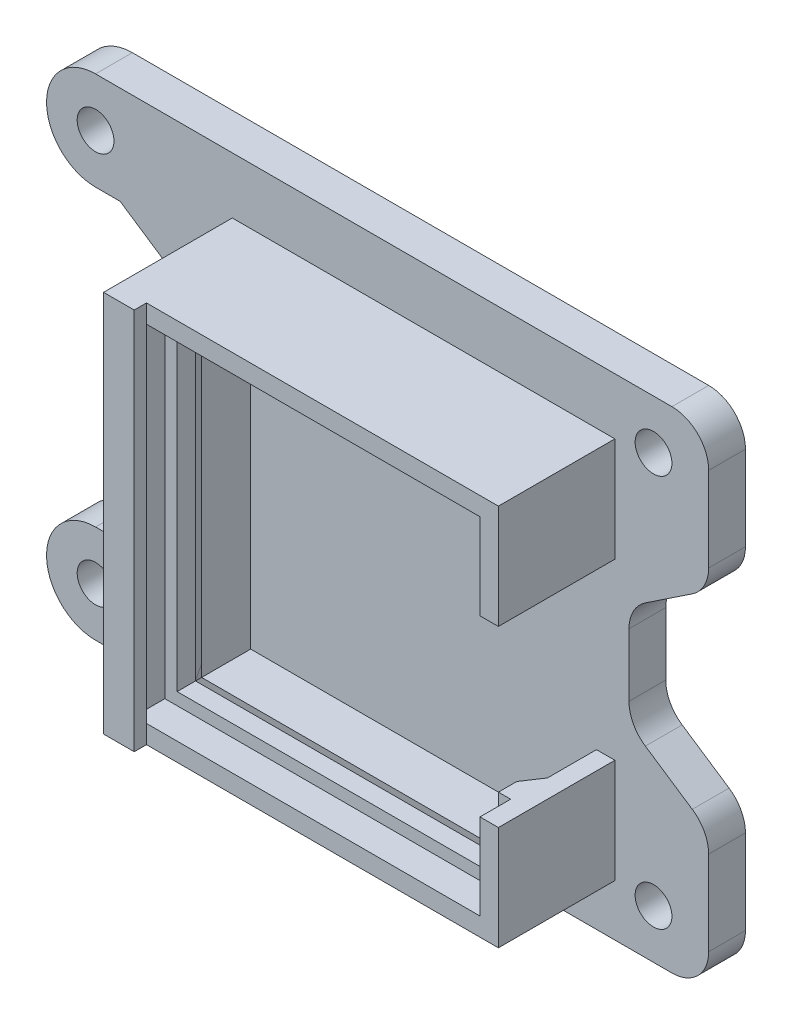
SolidWorks part; units mm, degrees
ref_plane "Alzado" through (0, 0, 0) normal (0, 0, 1) x (1, 0, 0)
ref_plane "Planta" through (0, 0, 0) normal (0, 1, 0) x (1, 0, 0)
ref_plane "Vista lateral" through (0, 0, 0) normal (1, 0, 0) x (0, 0, -1)
sketch "Croquis1" plane through (0, 0, 0) normal (0, 0, 1) x (1, 0, 0)
  line L0 (-52.1973, 0.4619) -> (-52.1973, 4.4619) construction
  line L1 (-2.1973, 16.4619) -> (-44.1973, 16.4619) construction
  line L2 (-52.1973, 4.4619) -> (-50.1973, 4.4619)
  line L3 (-52.1973, -3.5381) -> (-5.1973, -3.5381)
  line L5 (-44.1973, 24.4619) -> (-44.1973, 8.4619)
  line L6 (-44.1973, 8.4619) -> (-50.1973, 4.4619)
  line L7 (-52.1973, 32.4619) -> (-52.1973, 28.4619) construction
  line L8 (-44.1973, 24.4619) -> (-50.1973, 28.4619)
  line L9 (-52.1973, 36.4619) -> (-5.1973, 36.4619)
  line L10 (-52.1973, 28.4619) -> (-50.1973, 28.4619)
  line L11 (-2.1973, -0.5381) -> (-2.1973, 6.3563)
  line L13 (-3.5332, 8.8525) -> (-7.3614, 11.4046)
  line L14 (-8.6973, 13.9008) -> (-8.6973, 19.023)
  line L15 (-3.5332, 24.0713) -> (-7.3614, 21.5191)
  line L16 (-2.1973, 33.4619) -> (-2.1973, 26.5674)
  arc A0 (-52.1973, 36.4619) -> (-52.1973, 28.4619) centre (-52.1973, 32.4619) ccw
  circle A1 centre (-6.6973, 32.4619) radius 1.5
  circle A2 centre (-52.1973, 0.4619) radius 1.5
  circle A3 centre (-6.6973, 0.4619) radius 1.5
  circle A4 centre (-52.1973, 32.4619) radius 1.5
  arc A5 (-5.1973, 36.4619) -> (-2.1973, 33.4619) centre (-5.1973, 33.4619) cw
  arc A6 (-52.1973, -3.5381) -> (-52.1973, 4.4619) centre (-52.1973, 0.4619) cw
  arc A7 (-5.1973, -3.5381) -> (-2.1973, -0.5381) centre (-5.1973, -0.5381) ccw
  arc A8 (-7.3614, 21.5191) -> (-8.6973, 19.023) centre (-5.6973, 19.023) ccw
  arc A9 (-8.6973, 13.9008) -> (-7.3614, 11.4046) centre (-5.6973, 13.9008) ccw
  arc A10 (-3.5332, 24.0713) -> (-2.1973, 26.5674) centre (-5.1973, 26.5674) ccw
  arc A11 (-2.1973, 6.3563) -> (-3.5332, 8.8525) centre (-5.1973, 6.3563) ccw
  point P22 (-2.1973, 36.4619)
  point P26 (-2.1973, -3.5381)
  point P32 (-8.6973, 16.4619)
  point P35 (-8.6973, 20.6286)
  point P41 (-2.1973, 24.9619)
  point P44 (-2.1973, 7.9619)
  dimension "D3" = 50
  dimension "D5" = 20
  dimension "D6" = 4
  dimension "D7" = 42
  dimension "D2" = 3
  dimension "D4" = 3
  dimension "D12" = 3
  dimension "D8" = 4
  dimension "D9" = 45.5
  dimension "D10" = 2
  dimension "D11" = 8
  dimension "D13" = 6.5
extrude "Saliente-Extruir1" add sketch "Croquis1" along normal blind 3
sketch "Croquis2" plane through (0, 0, 3) normal (0, 0, 1) x (1, 0, 0)
  line L0 (-52.1973, -3.5381) -> (-5.1973, -3.5381) construction
  line L1 (-39.5473, 30.3619) -> (-11.3473, 30.3619)
  line L2 (-39.5473, 30.3619) -> (-39.5473, 2.1619)
  line L3 (-39.5473, 2.1619) -> (-11.3473, 2.1619)
  line L4 (-11.3473, 30.3619) -> (-11.3473, 2.1619)
  line L6 (-44.1973, 24.4619) -> (-44.1973, 8.4619) construction
  line L8 (-39.5473, 2.1619) -> (-11.3473, 30.3619) construction
  line L10 (-41.0473, 0.6619) -> (-9.8473, 0.6619)
  line L11 (-41.0473, 0.6619) -> (-41.0473, 31.8619)
  line L12 (-41.0473, 31.8619) -> (-9.8473, 31.8619)
  line L13 (-9.8473, 0.6619) -> (-9.8473, 31.8619)
  line L14 (-41.0473, 0.6619) -> (-9.8473, 31.8619) construction
  line L15 (-41.0473, 31.8619) -> (-9.8473, 0.6619) construction
  point P8 (-25.4473, 16.2619)
  dimension "D5" = 1.5
  dimension "D1" = 28.2
  dimension "D2" = 28.2
  dimension "D3" = 5.7
  dimension "D4" = 4.65
  dimension "D6" = 1.5
extrude "Saliente-Extruir2" add sketch "Croquis2" along normal blind 9.5
sketch "Croquis3" plane through (0, 30.3619, 0) normal (0, -1, 0) x (1, 0, 0)
  line L0 (-39.5473, 7) -> (-11.3473, 7) construction
  line L1 (-39.5473, 12.5) -> (-39.5473, 3) construction
  line L2 (-11.3473, 12.5) -> (-11.3473, 3) construction
  line L4 (-11.3473, 3) -> (-39.5473, 3) construction
  dimension "D1" = 4
ref_plane "Plano1" through (0, 0, 7) normal (0, 0, 1) x (1, 0, 0)
sketch "Croquis4" plane through (0, 0, 7) normal (0, 0, 1) x (1, 0, 0)
  line L0 (-11.3473, 30.3619) -> (-39.5473, 2.1619) construction
  line L1 (-39.5473, 30.3619) -> (-11.3473, 30.3619)
  line L2 (-39.5473, 30.3619) -> (-39.5473, 2.1619)
  line L3 (-39.5473, 2.1619) -> (-11.3473, 2.1619)
  line L4 (-11.3473, 30.3619) -> (-11.3473, 2.1619)
  line L6 (-12.3473, 3.1619) -> (-38.5473, 3.1619)
  line L7 (-12.3473, 3.1619) -> (-12.3473, 29.3619)
  line L8 (-12.3473, 29.3619) -> (-38.5473, 29.3619)
  line L9 (-38.5473, 3.1619) -> (-38.5473, 29.3619)
  line L10 (-12.3473, 3.1619) -> (-38.5473, 29.3619) construction
  line L11 (-12.3473, 29.3619) -> (-38.5473, 3.1619) construction
  point P5 (-25.4473, 16.2619)
  dimension "D1" = 28.2
  dimension "D2" = 28.2
  dimension "D3" = 1
extrude "Saliente-Extruir3" add sketch "Croquis4" along normal blind 3
ref_plane "Plano2" through (0, 3.1619, 0) normal (0, -1, 0) x (-1, 0, 0)
sketch "Croquis6" plane through (0, 3.1619, 0) normal (0, -1, 0) x (-1, 0, 0)
  line L0 (38.5473, -8.5) -> (38.5473, -7)
  line L1 (38.5473, -10) -> (38.5473, -7) construction
  line L2 (38.5473, -7) -> (39.5473, -7) construction
  line L3 (39.5473, -7) -> (38.5473, -8.5)
  line L6 (38.5473, -7) -> (39.5473, -7)
sketch "Croquis7" plane through (0, 0, 10) normal (0, 0, 1) x (1, 0, 0)
  line L0 (-38.5473, 29.3619) -> (-39.5473, 30.3619) construction
  line L1 (-12.3473, 29.3619) -> (-11.3473, 30.3619) construction
  line L2 (-38.5473, 3.1619) -> (-39.5473, 2.1619) construction
  line L3 (-39.5473, 30.3619) -> (-39.5473, 2.1619) construction
  line L4 (-12.3473, 3.1619) -> (-11.3473, 2.1619) construction
  line L5 (-39.0473, 29.8619) -> (-11.8473, 29.8619)
  line L6 (-11.8473, 29.8619) -> (-11.8473, 2.6619)
  line L7 (-11.8473, 2.6619) -> (-39.0473, 2.6619)
  line L8 (-39.0473, 2.6619) -> (-39.0473, 29.8619)
sweep "Cortar-Barrer1" cut profiles "Croquis6" path "Croquis7"
sketch "Croquis8" plane through (0, 0, 10) normal (0, 0, 1) x (1, 0, 0)
  line L8 (-11.3473, 30.3619) -> (-39.5473, 30.3619) construction
  line L9 (-30.5473, 30.3619) -> (-23.3473, 30.3619)
  line L10 (-30.5473, 30.3619) -> (-30.5473, 29.3619)
  line L11 (-30.5473, 29.3619) -> (-23.3473, 29.3619)
  line L12 (-23.3473, 30.3619) -> (-23.3473, 29.3619)
  line L13 (-12.3473, 29.3619) -> (-38.5473, 29.3619) construction
  line L14 (-39.5473, 30.3619) -> (-39.5473, 2.1619) construction
  line L15 (-11.3473, 2.1619) -> (-11.3473, 30.3619) construction
  dimension "D1" = 9
  dimension "D2" = 12
extrude "Cortar-Extruir1" cut sketch "Croquis8" against normal up to vertex
sketch "Croquis9" plane through (0, 0, 12.5) normal (0, 0, 1) x (1, 0, 0)
  line L0 (-9.8473, 0.6619) -> (-9.8473, 31.8619) construction
  line L1 (-9.8473, 9.1619) -> (-15.475, 9.1619)
  line L2 (-9.8473, 9.1619) -> (-9.8473, 23.3619)
  line L3 (-9.8473, 23.3619) -> (-15.475, 23.3619)
  line L4 (-15.475, 9.1619) -> (-15.475, 23.3619)
  line L5 (-39.5473, 30.3619) -> (-11.3473, 30.3619) construction
  line L6 (-39.5473, 2.1619) -> (-11.3473, 2.1619) construction
  dimension "D1" = 7
  dimension "D2" = 7
extrude "Cortar-Extruir2" cut sketch "Croquis9" against normal up to vertex
sketch "Croquis10" plane through (0, 0, 12.5) normal (0, 0, 1) x (1, 0, 0)
  line L0 (-9.8473, 31.8619) -> (-41.0473, 31.8619) construction
  line L1 (-41.0473, 0.6619) -> (-38.5473, 0.6619)
  line L2 (-41.0473, 0.6619) -> (-41.0473, 31.8619)
  line L3 (-41.0473, 31.8619) -> (-38.5473, 31.8619)
  line L4 (-38.5473, 0.6619) -> (-38.5473, 31.8619)
  dimension "D1" = 2.5
extrude "Saliente-Extruir4" add sketch "Croquis10" along normal blind 1
